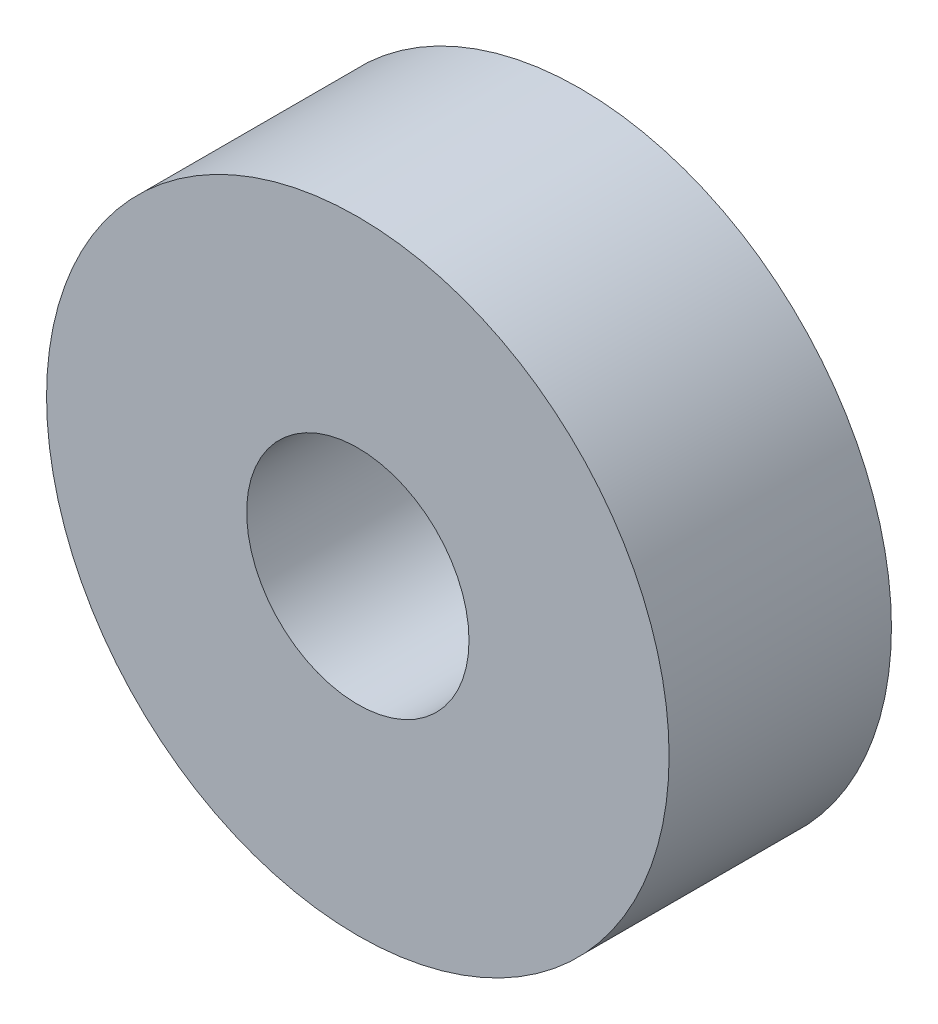
SolidWorks part; units mm, degrees
ref_plane "Front Plane" through (0, 0, 0) normal (0, 0, 1) x (1, 0, 0)
ref_plane "Top Plane" through (0, 0, 0) normal (0, 1, 0) x (1, 0, 0)
ref_plane "Right Plane" through (0, 0, 0) normal (1, 0, 0) x (0, 0, -1)
sketch "Sketch1" plane through (0, 0, 0) normal (0, 0, 1) x (1, 0, 0)
  circle A0 centre (0, 0) radius 2.5
  circle A1 centre (0, 0) radius 7
  dimension "D1" = 14
  dimension "D2" = 5
extrude "Boss-Extrude1" add sketch "Sketch1" along normal blind 5
